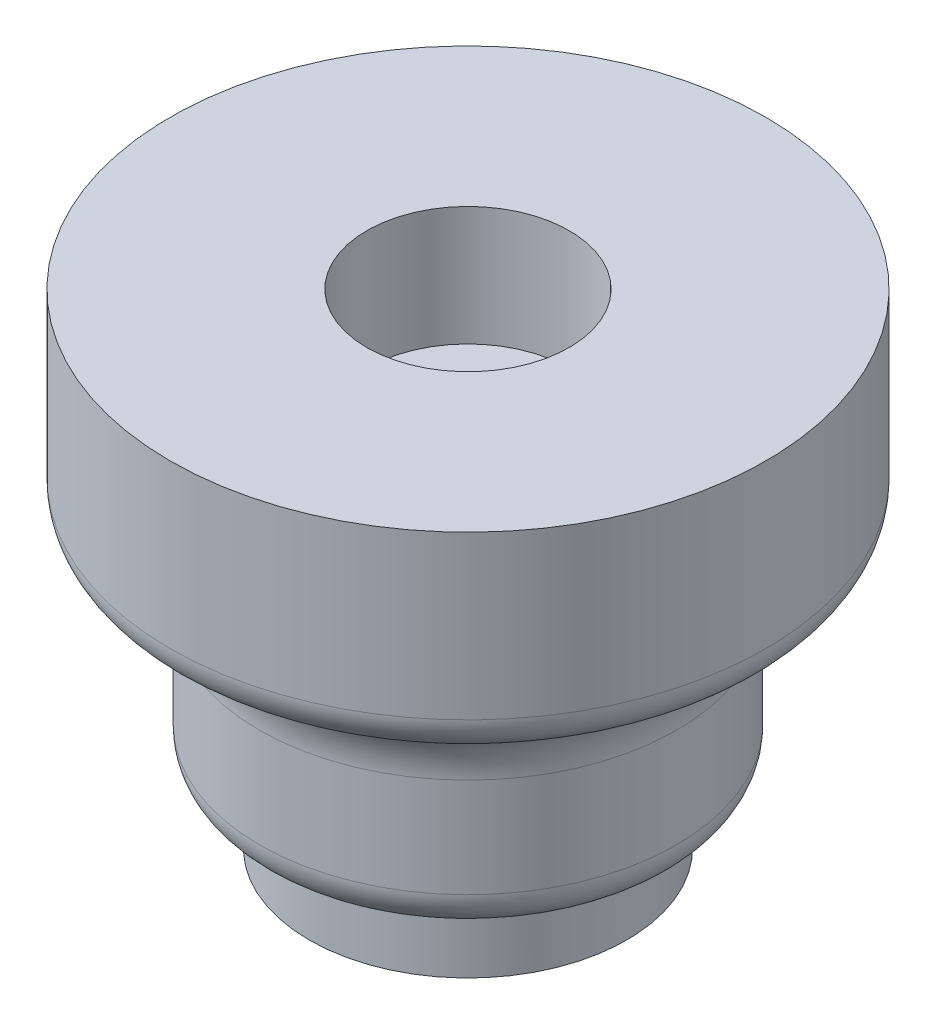
SolidWorks part; units mm, degrees
ref_plane "Front Plane" through (0, 0, 0) normal (0, 0, 1) x (1, 0, 0)
ref_plane "Top Plane" through (0, 0, 0) normal (0, 1, 0) x (1, 0, 0)
ref_plane "Right Plane" through (0, 0, 0) normal (1, 0, 0) x (0, 0, -1)
sketch "Sketch1" plane through (0, 0, 0) normal (0, 1, 0) x (1, 0, 0)
  circle A0 centre (0, 0) radius 5.25
extrude "Boss-Extrude1" add sketch "Sketch1" along normal blind 5.5
sketch "Sketch2" plane through (0, 0, 0) normal (0, -1, 0) x (1, 0, 0)
  circle A0 centre (0, 0) radius 4
extrude "Boss-Extrude2" add sketch "Sketch2" along normal blind 1.7
fillet "Fillet1" radius 0.15 1 edges at (0, 0, -4)
sketch "Sketch3" plane through (0, 5.5, 0) normal (0, 1, 0) x (1, 0, 0)
  circle A0 centre (0, 0) radius 7.5
  dimension "D1" = 15
extrude "Boss-Extrude3" add sketch "Sketch3" along normal blind 5
sketch "Sketch4" plane through (0, 10.5, 0) normal (0, 1, 0) x (1, 0, 0)
  circle A0 centre (0, 0) radius 2.55
  dimension "D1" = 5.1
extrude "Cut-Extrude1" cut sketch "Sketch4" against normal blind 3
sketch "Sketch5" plane through (0, -1.7, 0) normal (0, -1, 0) x (1, 0, 0)
  line L1 (2.7135, 0) -> (1.3568, 2.35)
  line L2 (1.3568, 2.35) -> (-1.3568, 2.35)
  line L3 (-1.3568, 2.35) -> (-2.7135, 0)
  line L4 (-2.7135, 0) -> (-1.3568, -2.35)
  line L5 (-1.3568, -2.35) -> (1.3568, -2.35)
  line L6 (1.3568, -2.35) -> (2.7135, 0)
  circle A0 centre (0, 0) radius 2.35 construction
  dimension "D1" = 4.7
extrude "Cut-Extrude2" cut sketch "Sketch5" against normal blind 4.7
fillet "Fillet2" radius 2 1 edges at (0, 5.5, 5.25)
fillet "Fillet3" radius 1 1 edges at (0, 0, 5.25)
fillet "Fillet4" radius 1 1 edges at (0, 5.5, 7.5)
